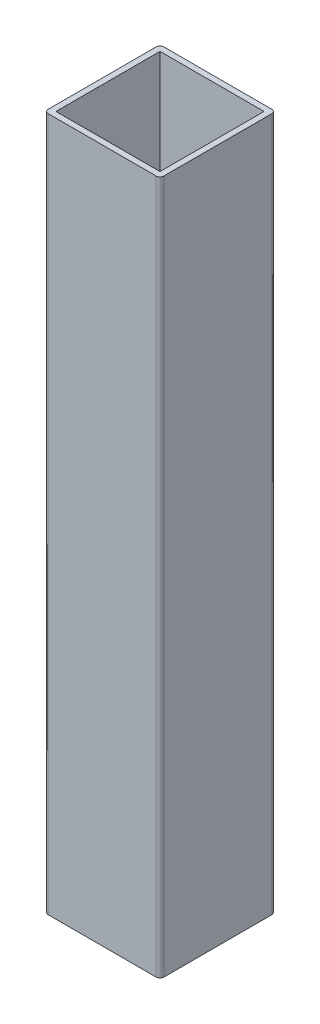
SolidWorks part; units mm, degrees
material "AISI 1020"
ref_plane "Plano frontal" through (0, 0, 0) normal (0, 0, 1) x (1, 0, 0)
ref_plane "Plano superior" through (0, 0, 0) normal (0, 1, 0) x (1, 0, 0)
ref_plane "Plano direito" through (0, 0, 0) normal (1, 0, 0) x (0, 0, -1)
sketch "Esboço1" plane through (0, 0, 0) normal (0, 1, 0) x (1, 0, 0)
  line L0 (-27, 27) -> (27, 27)
  line L1 (-28, -30) -> (28, -30)
  line L2 (-30, -28) -> (-30, 28)
  line L3 (-28, 30) -> (28, 30)
  line L4 (30, -28) -> (30, 28)
  line L5 (-30, -30) -> (30, 30) construction
  line L6 (-30, 30) -> (30, -30) construction
  line L7 (27, -27) -> (27, 27)
  line L8 (-27, -27) -> (27, -27)
  line L9 (-27, -27) -> (-27, 27)
  arc A0 (-30, -28) -> (-28, -30) centre (-28, -28) ccw
  arc A1 (28, -30) -> (30, -28) centre (28, -28) ccw
  arc A2 (28, 30) -> (30, 28) centre (28, 28) cw
  arc A3 (-30, 28) -> (-28, 30) centre (-28, 28) cw
  arc A4 (27, 27) -> (27, 27) centre (27, 27) cw
  arc A5 (27, -27) -> (27, -27) centre (27, -27) ccw
  arc A6 (-27, -27) -> (-27, -27) centre (-27, -27) ccw
  arc A7 (-27, 27) -> (-27, 27) centre (-27, 27) cw
  point P0 (0, 0)
  dimension "D3" = 2
  dimension "D1" = 60
  dimension "D2" = 60
  dimension "D4" = 3
extrude "Ressalto-extrusão1" add sketch "Esboço1" along normal mid plane 360
